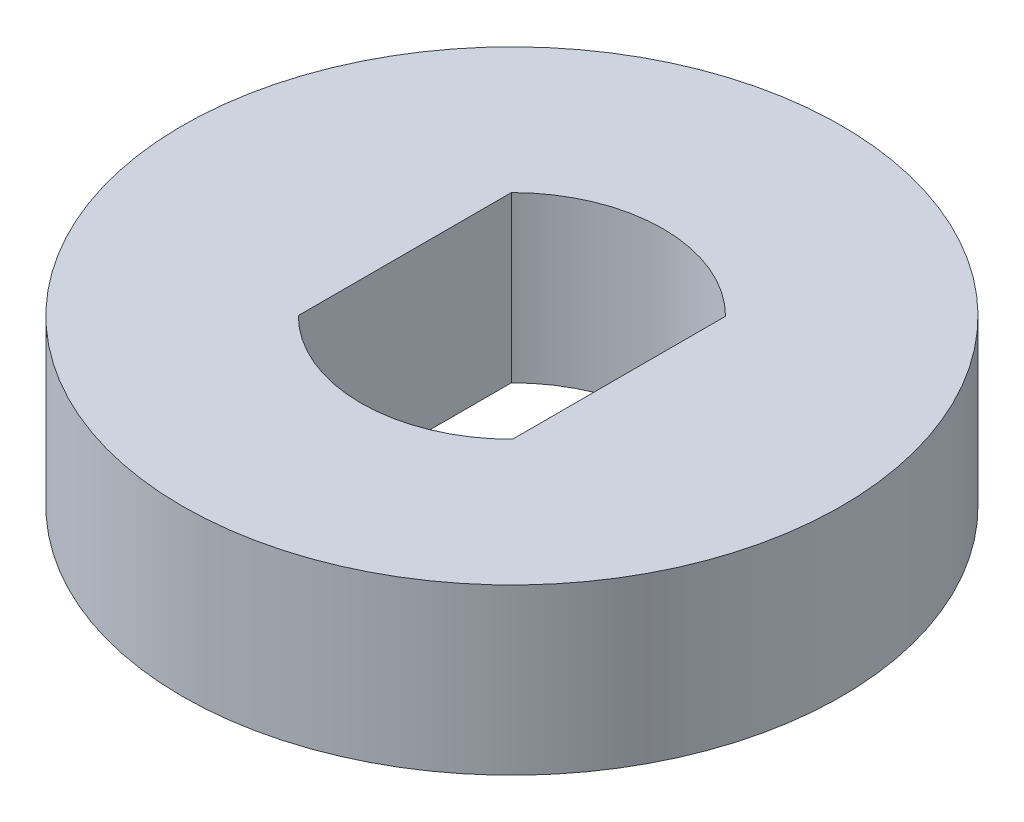
SolidWorks part; units mm, degrees
ref_plane "Front Plane" through (0, 0, 0) normal (0, 0, 1) x (1, 0, 0)
ref_plane "Top Plane" through (0, 0, 0) normal (0, 1, 0) x (1, 0, 0)
ref_plane "Right Plane" through (0, 0, 0) normal (1, 0, 0) x (0, 0, -1)
sketch "Sketch1" plane through (0, 0, 0) normal (0, 1, 0) x (1, 0, 0)
  line L1 (-1.95, 8) -> (1.95, 8)
  line L2 (-1.95, 8) -> (-1.95, -8)
  line L3 (-1.95, -8) -> (1.95, -8)
  line L4 (1.95, 8) -> (1.95, -8)
  circle A0 centre (0, 0) radius 2.75
  circle A1 centre (0, 0) radius 6
  dimension "D1" = 5.5
  dimension "D2" = 12
  dimension "D3" = 3.9
  dimension "D4" = 1.95
  dimension "D5" = 8
  dimension "D6" = 8
extrude "Boss-Extrude1" add sketch "Sketch1" along normal blind 3 contours L4 A0 | L2 A1 L4 A0 | L2 A1 A0 | L4 A1 L2 A0 | L4 A1 A0 | L2 A0
